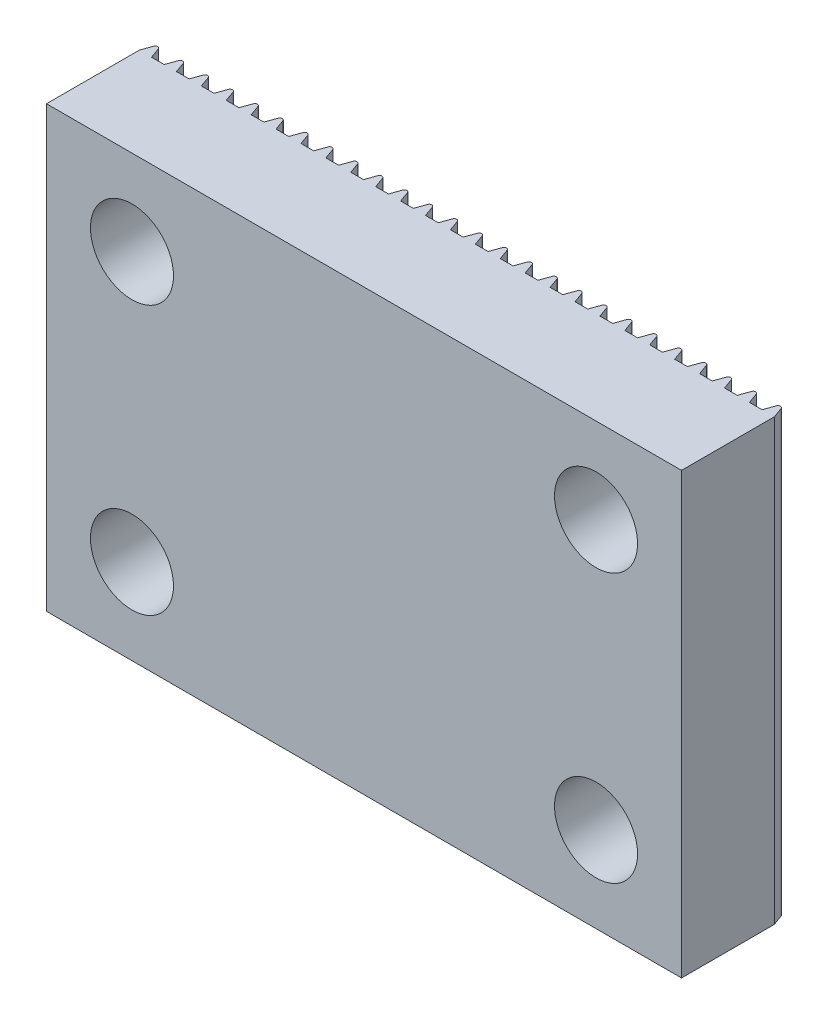
SolidWorks part; units mm, degrees
ref_plane "前视基准面" through (0, 0, 0) normal (0, 0, 1) x (1, 0, 0)
ref_plane "上视基准面" through (0, 0, 0) normal (0, 1, 0) x (1, 0, 0)
ref_plane "右视基准面" through (0, 0, 0) normal (1, 0, 0) x (0, 0, -1)
sketch "草图1" plane through (0, 0, 0) normal (0, 1, 0) x (1, 0, 0)
  line L0 (0, 3.8) -> (0.1558, 4.2363)
  line L1 (0, 0) -> (26, 0)
  line L2 (0, 0) -> (0, 3.8)
  line L3 (0, 3.8) -> (26, 3.8)
  line L4 (26, 0) -> (26, 3.8)
  line L5 (0.3442, 4.2363) -> (0.5, 3.8)
  line L6 (0.25, 5.112) -> (0.25, 2.8313) construction
  line L7 (1.02, 3.8) -> (1.1758, 4.2363)
  line L8 (1.3642, 4.2363) -> (1.52, 3.8)
  line L9 (2.04, 3.8) -> (2.1958, 4.2363)
  line L10 (2.3842, 4.2363) -> (2.54, 3.8)
  line L11 (3.06, 3.8) -> (3.2158, 4.2363)
  line L12 (3.4042, 4.2363) -> (3.56, 3.8)
  line L13 (4.08, 3.8) -> (4.2358, 4.2363)
  line L14 (4.4242, 4.2363) -> (4.58, 3.8)
  line L15 (5.1, 3.8) -> (5.2558, 4.2363)
  line L16 (5.4442, 4.2363) -> (5.6, 3.8)
  line L17 (6.12, 3.8) -> (6.2758, 4.2363)
  line L18 (6.4642, 4.2363) -> (6.62, 3.8)
  line L19 (7.14, 3.8) -> (7.2958, 4.2363)
  line L20 (7.4842, 4.2363) -> (7.64, 3.8)
  line L21 (8.16, 3.8) -> (8.3158, 4.2363)
  line L22 (8.5042, 4.2363) -> (8.66, 3.8)
  line L23 (9.18, 3.8) -> (9.3358, 4.2363)
  line L24 (9.5242, 4.2363) -> (9.68, 3.8)
  line L25 (10.2, 3.8) -> (10.3558, 4.2363)
  line L26 (10.5442, 4.2363) -> (10.7, 3.8)
  line L27 (11.22, 3.8) -> (11.3758, 4.2363)
  line L28 (11.5642, 4.2363) -> (11.72, 3.8)
  line L29 (12.24, 3.8) -> (12.3958, 4.2363)
  line L30 (12.5842, 4.2363) -> (12.74, 3.8)
  line L31 (13.26, 3.8) -> (13.4158, 4.2363)
  line L32 (13.6042, 4.2363) -> (13.76, 3.8)
  line L33 (14.28, 3.8) -> (14.4358, 4.2363)
  line L34 (14.6242, 4.2363) -> (14.78, 3.8)
  line L35 (15.3, 3.8) -> (15.4558, 4.2363)
  line L36 (15.6442, 4.2363) -> (15.8, 3.8)
  line L37 (16.32, 3.8) -> (16.4758, 4.2363)
  line L38 (16.6642, 4.2363) -> (16.82, 3.8)
  line L39 (17.34, 3.8) -> (17.4958, 4.2363)
  line L40 (17.6842, 4.2363) -> (17.84, 3.8)
  line L41 (18.36, 3.8) -> (18.5158, 4.2363)
  line L42 (18.7042, 4.2363) -> (18.86, 3.8)
  line L43 (19.38, 3.8) -> (19.5358, 4.2363)
  line L44 (19.7242, 4.2363) -> (19.88, 3.8)
  line L45 (20.4, 3.8) -> (20.5558, 4.2363)
  line L46 (20.7442, 4.2363) -> (20.9, 3.8)
  line L47 (21.42, 3.8) -> (21.5758, 4.2363)
  line L48 (21.7642, 4.2363) -> (21.92, 3.8)
  line L49 (22.44, 3.8) -> (22.5958, 4.2363)
  line L50 (22.7842, 4.2363) -> (22.94, 3.8)
  line L51 (23.46, 3.8) -> (23.6158, 4.2363)
  line L52 (23.8042, 4.2363) -> (23.96, 3.8)
  line L53 (24.48, 3.8) -> (24.6358, 4.2363)
  line L54 (24.8242, 4.2363) -> (24.98, 3.8)
  line L55 (25.5, 3.8) -> (25.6558, 4.2363)
  line L56 (25.8442, 4.2363) -> (26, 3.8)
  arc A0 (0.3442, 4.2363) -> (0.1558, 4.2363) centre (0.25, 4.2027) ccw
  arc A1 (1.3642, 4.2363) -> (1.1758, 4.2363) centre (1.27, 4.2027) ccw
  arc A2 (2.3842, 4.2363) -> (2.1958, 4.2363) centre (2.29, 4.2027) ccw
  arc A3 (3.4042, 4.2363) -> (3.2158, 4.2363) centre (3.31, 4.2027) ccw
  arc A4 (4.4242, 4.2363) -> (4.2358, 4.2363) centre (4.33, 4.2027) ccw
  arc A5 (5.4442, 4.2363) -> (5.2558, 4.2363) centre (5.35, 4.2027) ccw
  arc A6 (6.4642, 4.2363) -> (6.2758, 4.2363) centre (6.37, 4.2027) ccw
  arc A7 (7.4842, 4.2363) -> (7.2958, 4.2363) centre (7.39, 4.2027) ccw
  arc A8 (8.5042, 4.2363) -> (8.3158, 4.2363) centre (8.41, 4.2027) ccw
  arc A9 (9.5242, 4.2363) -> (9.3358, 4.2363) centre (9.43, 4.2027) ccw
  arc A10 (10.5442, 4.2363) -> (10.3558, 4.2363) centre (10.45, 4.2027) ccw
  arc A11 (11.5642, 4.2363) -> (11.3758, 4.2363) centre (11.47, 4.2027) ccw
  arc A12 (12.5842, 4.2363) -> (12.3958, 4.2363) centre (12.49, 4.2027) ccw
  arc A13 (13.6042, 4.2363) -> (13.4158, 4.2363) centre (13.51, 4.2027) ccw
  arc A14 (14.6242, 4.2363) -> (14.4358, 4.2363) centre (14.53, 4.2027) ccw
  arc A15 (15.6442, 4.2363) -> (15.4558, 4.2363) centre (15.55, 4.2027) ccw
  arc A16 (16.6642, 4.2363) -> (16.4758, 4.2363) centre (16.57, 4.2027) ccw
  arc A17 (17.6842, 4.2363) -> (17.4958, 4.2363) centre (17.59, 4.2027) ccw
  arc A18 (18.7042, 4.2363) -> (18.5158, 4.2363) centre (18.61, 4.2027) ccw
  arc A19 (19.7242, 4.2363) -> (19.5358, 4.2363) centre (19.63, 4.2027) ccw
  arc A20 (20.7442, 4.2363) -> (20.5558, 4.2363) centre (20.65, 4.2027) ccw
  arc A21 (21.7642, 4.2363) -> (21.5758, 4.2363) centre (21.67, 4.2027) ccw
  arc A22 (22.7842, 4.2363) -> (22.5958, 4.2363) centre (22.69, 4.2027) ccw
  arc A23 (23.8042, 4.2363) -> (23.6158, 4.2363) centre (23.71, 4.2027) ccw
  arc A24 (24.8242, 4.2363) -> (24.6358, 4.2363) centre (24.73, 4.2027) ccw
  arc A25 (25.8442, 4.2363) -> (25.6558, 4.2363) centre (25.75, 4.2027) ccw
  point P12 (0.25, 4.5)
  dimension "D5" = 0.1
  dimension "D1" = 3.8
  dimension "D2" = 0.7
  dimension "D3" = 26
  dimension "D4" = 0.5
  dimension "D6" = 26
extrude "凸台-拉伸1" add sketch "草图1" along normal blind 18 contours L10 A2 L9 L3 | L6 A0 L0 L3 | A0 L6 L3 L5 | L8 A1 L7 L3 | L12 A3 L11 L3 | L1 L4 L3 | L14 A4 L13 L3 | L16 A5 L15 L3 | L18 A6 L17 L3 | L20 A7 L19 L3 | L22 A8 L21 L3 | L24 A9 L23 L3 | L26 A10 L25 L3 | L28 A11 L27 L3 | L30 A12 L29 L3 | L32 A13 L31 L3 | L34 A14 L33 L3 | L36 A15 L35 L3 | L38 A16 L37 L3 | L40 A17 L39 L3 | L42 A18 L41 L3 | L44 A19 L43 L3 | L46 A20 L45 L3 | L48 A21 L47 L3 | L50 A22 L49 L3 | L52 A23 L51 L3 | L54 A24 L53 L3 | L56 A25 L55 L3
sketch "草图2" plane through (0, 0, 0) normal (0, 0, 1) x (1, 0, 0)
  line L0 (0, 9) -> (26, 9) construction
  line L1 (0, 18) -> (0, 0) construction
  line L2 (26, 18) -> (26, 0) construction
  line L3 (13, 18) -> (13, 0) construction
  line L4 (0, 18) -> (26, 18) construction
  line L5 (0, 0) -> (26, 0) construction
  circle A0 centre (3.5, 14.5) radius 1.7
  circle A1 centre (3.5, 3.5) radius 1.7
  circle A2 centre (22.5, 3.5) radius 1.7
  circle A3 centre (22.5, 14.5) radius 1.7
  dimension "D1" = 3.4
  dimension "D2" = 11
  dimension "D3" = 19
extrude "切除-拉伸1" cut sketch "草图2" against normal up to next
